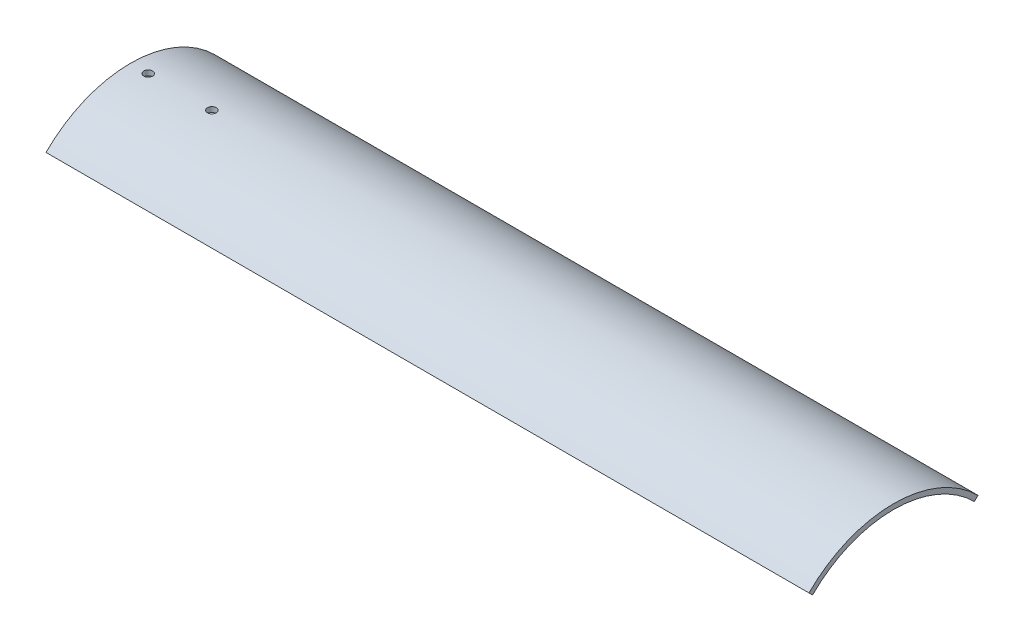
SolidWorks part; units mm, degrees
material "PVC Rigid"
ref_plane "Front Plane" through (0, 0, 0) normal (0, 0, 1) x (1, 0, 0)
ref_plane "Top Plane" through (0, 0, 0) normal (0, 1, 0) x (1, 0, 0)
ref_plane "Right Plane" through (0, 0, 0) normal (1, 0, 0) x (0, 0, -1)
sketch "Sketch1" plane through (0, 0, 0) normal (1, 0, 0) x (0, 0, -1)
  line L0 (31.8198, 31.8198) -> (33.234, 33.234)
  line L1 (-31.8198, 31.8198) -> (-33.234, 33.234)
  line L2 (0, 0) -> (0, 47) construction
  arc A0 (31.8198, 31.8198) -> (-31.8198, 31.8198) centre (0, 0) ccw
  arc A1 (33.234, 33.234) -> (-33.234, 33.234) centre (0, 0) ccw
  point P9 (0, 47)
  dimension "D2" = 45
  dimension "D1" = 2
  dimension "D4" = 90
extrude "Boss-Extrude1" add sketch "Sketch1" along normal blind 300
sketch "Sketch3" plane through (0, 0, -3.699) normal (0, 1, 0) x (1, 0, 0)
  line L1 (0, 29.535) -> (0, -36.933) construction
  line L2 (-8.3491, -3.699) -> (8.3491, -3.699) construction
  line L3 (0, -3.699) -> (300, -3.699) construction
  line L4 (300, -36.933) -> (300, 29.535) construction
  circle A0 centre (7, -3.699) radius 1.75
  circle A1 centre (32, -3.699) radius 1.75
  dimension "D1" = 3.5
  dimension "D2" = 25
  dimension "D3" = 7
extrude "Cut-Extrude1" cut sketch "Sketch3" along normal through all
